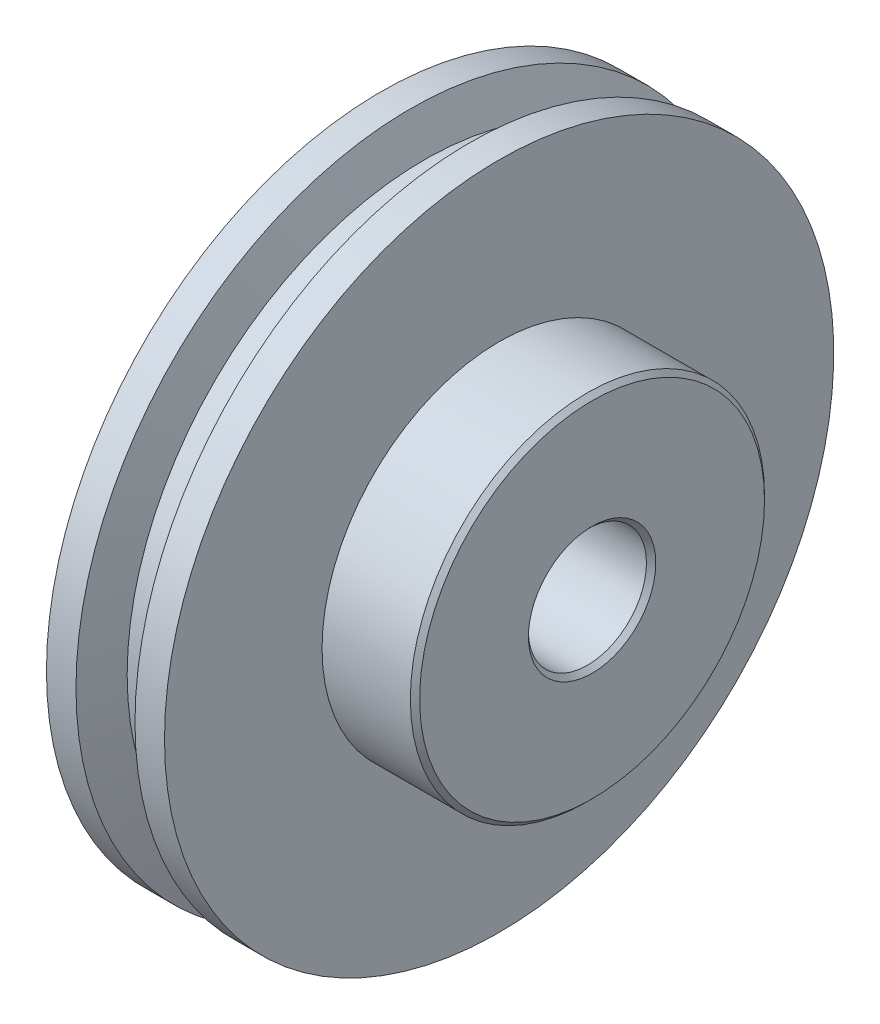
SolidWorks part; units mm, degrees
material "Polybutadiene (PB)"
ref_plane "Front Plane" through (0, 0, 0) normal (0, 0, 1) x (1, 0, 0)
ref_plane "Top Plane" through (0, 0, 0) normal (0, 1, 0) x (1, 0, 0)
ref_plane "Right Plane" through (0, 0, 0) normal (1, 0, 0) x (0, 0, -1)
sketch "Sketch2" plane through (0, 0, 0) normal (0, 0, 1) x (1, 0, 0)
  line L0 (0, 0) -> (59.7537, 0) construction
  line L1 (0, 0) -> (0, 50.4348) construction
  line L2 (-3.175, 3.175) -> (3.175, 3.175)
  line L3 (3.175, 3.175) -> (3.175, 18)
  line L4 (-3.175, 3.175) -> (-3.175, 18)
  line L5 (-3.175, 18) -> (-1.5875, 18)
  line L6 (-1.5875, 18) -> (-0.8336, 16)
  line L7 (-0.8336, 16) -> (0.8336, 16)
  line L8 (0.8336, 16) -> (1.5875, 18)
  line L9 (1.5875, 18) -> (3.175, 18)
  dimension "D1" = 3.175
  dimension "D2" = 18
  dimension "D3" = 6.35
  dimension "D4" = 2
  dimension "D6" = 3.175
revolve "Revolve1" add sketch "Sketch2" angle 360 about L0
sketch "Sketch3" plane through (3.175, 0, 0) normal (1, 0, 0) x (0, 0, -1)
  circle A0 centre (0, 0) radius 9.525
  dimension "D1" = 19.05
extrude "Boss-Extrude1" add sketch "Sketch3" along normal blind 5
sketch "Sketch4" plane through (8.175, 0, 0) normal (1, 0, 0) x (0, 0, -1)
  circle A0 centre (0, 0) radius 3.175
  dimension "D1" = 6.35
extrude "Cut-Extrude1" cut sketch "Sketch4" against normal through all
chamfer "Chamfer1" distance 0.25 angle 45 3 edges at (-3.175, 0, 3.175) (8.175, 0, -3.175) (8.175, 0, -9.525)
